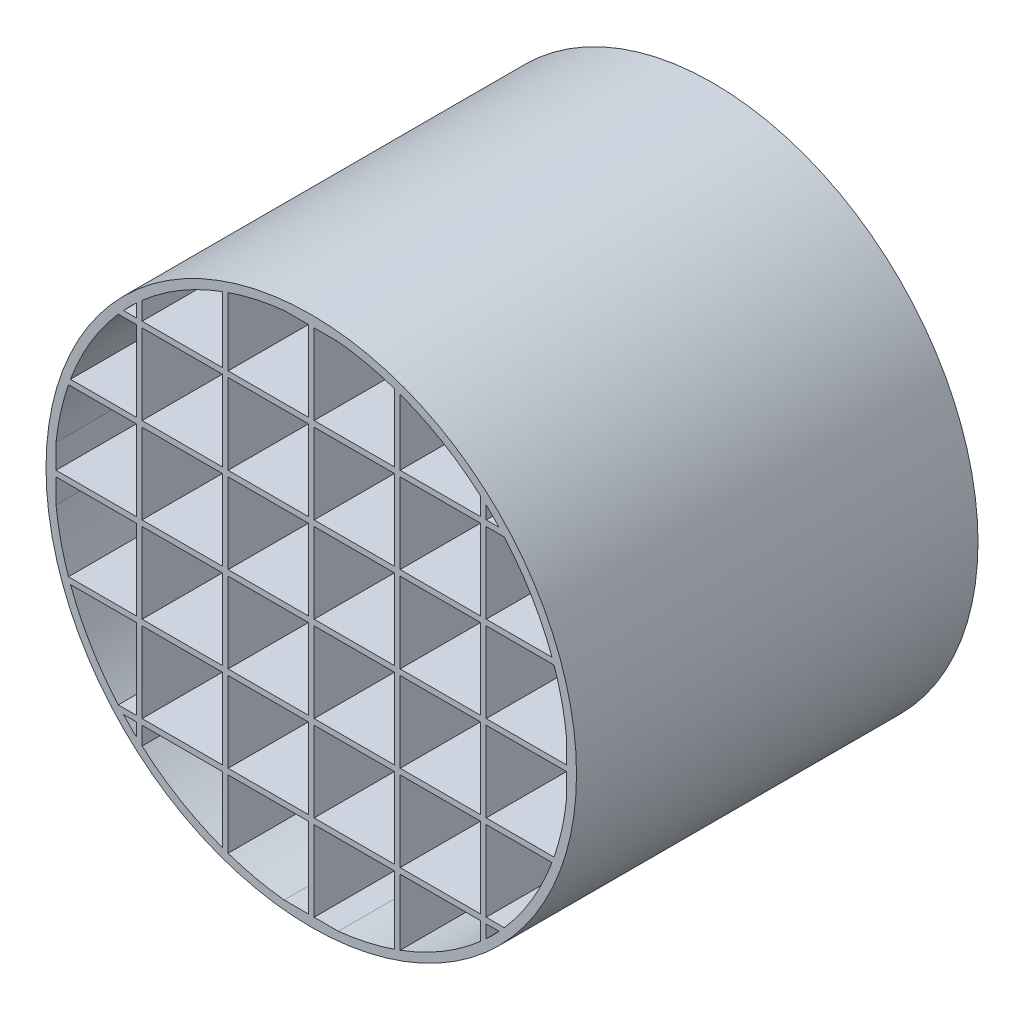
SolidWorks part; units mm, degrees
ref_plane "前视基准面" through (0, 0, 0) normal (0, 0, 1) x (1, 0, 0)
ref_plane "上视基准面" through (0, 0, 0) normal (0, 1, 0) x (1, 0, 0)
ref_plane "右视基准面" through (0, 0, 0) normal (1, 0, 0) x (0, 0, -1)
sketch "草图7" plane through (0, 0, 0) normal (0, 0, 1) x (1, 0, 0)
  line L1 (0, 0) -> (400, 0)
  line L2 (0, 0) -> (0, 400)
  line L3 (0, 400) -> (400, 400)
  line L4 (400, 0) -> (400, 400)
  dimension "D1" = 400
  dimension "D2" = 400
extrude "凸台-拉伸1" add sketch "草图7" along normal blind 3
sketch "草图8" plane through (0, 0, 3) normal (0, 0, 1) x (1, 0, 0)
  line L0 (10, 390) -> (390, 390)
  line L1 (400, 0) -> (400, 400) construction
  line L2 (0, 400) -> (0, 0) construction
  line L3 (400, 400) -> (0, 400) construction
  line L4 (10, 390) -> (10, 388)
  line L5 (10, 388) -> (390, 388)
  line L6 (390, 388) -> (390, 390)
  dimension "D1" = 10
  dimension "D2" = 10
  dimension "D3" = 10
  dimension "D4" = 2
extrude "凸台-拉伸2" add sketch "草图8" along normal blind 140
sketch "草图9" plane through (0, 0, 3) normal (0, 0, 1) x (1, 0, 0)
  line L1 (10, 390) -> (12, 390)
  line L2 (10, 390) -> (10, 8)
  line L3 (10, 8) -> (12, 8)
  line L4 (12, 390) -> (12, 8)
  dimension "D1" = 2
  dimension "D2" = 382
extrude "凸台-拉伸3" add sketch "草图9" along normal blind 140
pattern_linear "阵列(线性)1" count 12 spacing 30 along (1, 0, 0) of "凸台-拉伸3"
pattern_linear "阵列(线性)3" count 12 spacing 30 along (0, -1, 0) of "凸台-拉伸2"
sketch "草图11" plane through (0, 0, 0) normal (0, 0, -1) x (-1, 0, 0)
  line L4 (0, 0) -> (0, 400)
  line L5 (0, 0) -> (0, 400)
  line L6 (0, 400) -> (-400, 400)
  line L7 (0, 400) -> (-400, 400)
  line L12 (-400, 400) -> (-400, 0)
  line L13 (-400, 400) -> (-400, 0)
  line L14 (-400, 0) -> (0, 0)
  line L15 (-400, 0) -> (0, 0)
  dimension "D1" = 0
extrude "切除-拉伸1" cut sketch "草图11" against normal blind 3
sketch "草图12" plane through (0, 0, 3) normal (0, 0, -1) x (-1, 0, 0)
  line L0 (-190, 238) -> (-190, 210) construction
  circle A0 centre (-191, 208.9584) radius 90
  circle A1 centre (-191, 208.9584) radius 300
  dimension "D2" = 180
  dimension "D3" = 600
  dimension "D1" = 1
extrude "切除-拉伸2" cut sketch "草图12" against normal through all both and the other way through all
sketch "草图13" plane through (0, 0, 3) normal (0, 0, -1) x (-1, 0, 0)
  line L0 (-190, 238) -> (-190, 210) construction
  line L1 (-162, 208) -> (-190, 208) construction
  circle A0 centre (-191, 209) radius 89.5
  circle A1 centre (-191, 209) radius 92.5
  dimension "D4" = 179
  dimension "D1" = 1
  dimension "D2" = 1
  dimension "D3" = 3
extrude "凸台-拉伸8" add sketch "草图13" against normal up to surface (140 mm away) up to face at (236, 254, 143)
